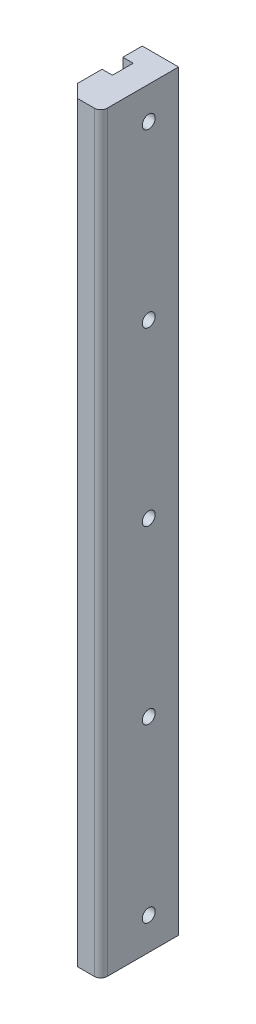
SolidWorks part; units mm, degrees
ref_plane "Front Plane" through (0, 0, 0) normal (0, 0, 1) x (1, 0, 0)
ref_plane "Top Plane" through (0, 0, 0) normal (0, 1, 0) x (1, 0, 0)
ref_plane "Right Plane" through (0, 0, 0) normal (1, 0, 0) x (0, 0, -1)
sketch "Sketch1" plane through (0, 0, 0) normal (0, 1, 0) x (1, 0, 0)
  line L0 (0, 0) -> (0, 60)
  line L1 (0, 60) -> (-28, 60)
  line L2 (-28, 60) -> (-28, 45)
  line L3 (-28, 45) -> (-20, 45)
  line L4 (-20, 45) -> (-20, 29)
  line L5 (-20, 29) -> (-28, 29)
  line L6 (-28, 29) -> (-28, 10)
  line L7 (0, 0) -> (-18, 0)
  line L8 (-18, 0) -> (-28, 10)
extrude "Boss-Extrude1" add sketch "Sketch1" along normal blind 580 contours L8 L6 L5 L4 L3 L2 L1 L0 L7
sketch "Sketch2" plane through (0, 0, 0) normal (1, 0, 0) x (0, 0, -1)
  circle A1 centre (37, 25) radius 5
extrude "Cut-Extrude1" cut sketch "Sketch2" against normal blind 580
sketch "Sketch4" plane through (-20, 0, 0) normal (-1, 0, 0) x (0, 0, 1)
  circle A0 centre (-37, 157.5) radius 5
extrude "Cut-Extrude2" cut sketch "Sketch4" against normal blind 580
sketch "Sketch5" plane through (0, 0, 0) normal (1, 0, 0) x (0, 0, -1)
  circle A0 centre (37, 290) radius 5
extrude "Cut-Extrude3" cut sketch "Sketch5" against normal blind 580
sketch "Sketch6" plane through (0, 0, 0) normal (1, 0, 0) x (0, 0, -1)
  circle A0 centre (37, 422.5) radius 5
extrude "Cut-Extrude4" cut sketch "Sketch6" against normal blind 580
sketch "Sketch7" plane through (0, 0, 0) normal (1, 0, 0) x (0, 0, -1)
  circle A0 centre (37, 555) radius 5
extrude "Cut-Extrude5" cut sketch "Sketch7" against normal blind 580
fillet "Fillet3" radius 5 1 edges at (0, 290, 0)
